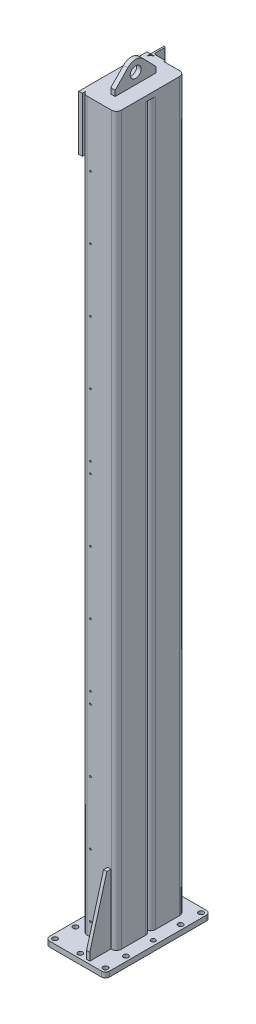
SolidWorks part; units mm, degrees
ref_plane "正面" through (0, 0, 0) normal (0, 0, 1) x (1, 0, 0)
ref_plane "平面" through (0, 0, 0) normal (0, 1, 0) x (1, 0, 0)
ref_plane "右側面" through (0, 0, 0) normal (1, 0, 0) x (0, 0, -1)
ref_plane "平面1" through (0, 19, 0) normal (0, 1, 0) x (1, 0, 0)
sketch "ｽｹｯﾁ2" plane through (0, 19, 0) normal (0, 1, 0) x (1, 0, 0)
  line L0 (44.5, -105) -> (-44.5, -105)
  line L1 (-62.5, -87) -> (-62.5, 2)
  line L2 (-44.5, 20) -> (44.5, 20)
  line L3 (62.5, 2) -> (62.5, -87)
  arc A0 (-44.5, -105) -> (-62.5, -87) centre (-44.5, -87) cw
  arc A1 (-62.5, 2) -> (-44.5, 20) centre (-44.5, 2) cw
  arc A2 (44.5, 20) -> (62.5, 2) centre (44.5, 2) cw
  arc A3 (62.5, -87) -> (44.5, -105) centre (44.5, -87) cw
extrude "ﾎﾞｽ - 押し出し1" add sketch "ｽｹｯﾁ2" along normal blind 2643
sketch "ｽｹｯﾁ3" plane through (0, 19, 0) normal (0, 1, 0) x (1, 0, 0)
  line L0 (44.5, 20) -> (-44.5, 20)
  line L1 (-62.5, 38) -> (-62.5, 127)
  line L2 (-44.5, 145) -> (44.5, 145)
  line L3 (62.5, 127) -> (62.5, 38)
  arc A0 (-44.5, 20) -> (-62.5, 38) centre (-44.5, 38) cw
  arc A1 (-62.5, 127) -> (-44.5, 145) centre (-44.5, 127) cw
  arc A2 (44.5, 145) -> (62.5, 127) centre (44.5, 127) cw
  arc A3 (62.5, 38) -> (44.5, 20) centre (44.5, 38) cw
extrude "ﾎﾞｽ - 押し出し2" add sketch "ｽｹｯﾁ3" along normal blind 2643
sketch "ｽｹｯﾁ4" plane through (0, 19, 0) normal (0, 1, 0) x (1, 0, 0)
  line L0 (44.5, -96) -> (-44.5, -96)
  line L1 (-53.5, -87) -> (-53.5, 2)
  line L2 (-44.5, 11) -> (44.5, 11)
  line L3 (53.5, 2) -> (53.5, -87)
  line L4 (44.5, 29) -> (-44.5, 29)
  line L5 (-53.5, 38) -> (-53.5, 127)
  line L6 (-44.5, 136) -> (44.5, 136)
  line L7 (53.5, 127) -> (53.5, 38)
  arc A0 (-44.5, -96) -> (-53.5, -87) centre (-44.5, -87) cw
  arc A1 (-53.5, 2) -> (-44.5, 11) centre (-44.5, 2) cw
  arc A2 (44.5, 11) -> (53.5, 2) centre (44.5, 2) cw
  arc A3 (53.5, -87) -> (44.5, -96) centre (44.5, -87) cw
  arc A4 (-44.5, 29) -> (-53.5, 38) centre (-44.5, 38) cw
  arc A5 (-53.5, 127) -> (-44.5, 136) centre (-44.5, 127) cw
  arc A6 (44.5, 136) -> (53.5, 127) centre (44.5, 127) cw
  arc A7 (53.5, 38) -> (44.5, 29) centre (44.5, 38) cw
extrude "ｶｯﾄ - 押し出し1" cut sketch "ｽｹｯﾁ4" against normal through all and the other way through all
sketch "ｽｹｯﾁ5" plane through (0, 0, 0) normal (0, 1, 0) x (1, 0, 0)
  line L0 (95, -192.5) -> (-95, -192.5)
  line L1 (-110, -177.5) -> (-110, 177.5)
  line L2 (-95, 192.5) -> (95, 192.5)
  line L3 (110, 177.5) -> (110, -177.5)
  arc A0 (-95, -192.5) -> (-110, -177.5) centre (-95, -177.5) cw
  arc A1 (-110, 177.5) -> (-95, 192.5) centre (-95, 177.5) cw
  arc A2 (95, 192.5) -> (110, 177.5) centre (95, 177.5) cw
  arc A3 (110, -177.5) -> (95, -192.5) centre (95, -177.5) cw
extrude "ﾎﾞｽ - 押し出し3" add sketch "ｽｹｯﾁ5" along normal blind 19
ref_plane "平面2" through (42.5, 0, 0) normal (1, 0, 0) x (0, 0, -1)
sketch "ｽｹｯﾁ7" plane through (42.5, 0, 0) normal (1, 0, 0) x (0, 0, -1)
  line L0 (-105, 19) -> (-105, 272)
  line L1 (-105, 272) -> (-120, 272)
  line L2 (-120, 272) -> (-182.5, 47)
  line L3 (-182.5, 47) -> (-182.5, 19)
  line L4 (-182.5, 19) -> (-105, 19)
extrude "ﾎﾞｽ - 押し出し4" add sketch "ｽｹｯﾁ7" against normal blind 12
sketch "ｽｹｯﾁ8" plane through (0, 19, 0) normal (0, 1, 0) x (1, 0, 0)
  line L0 (-62.5, 145) -> (-12.5, 145)
  line L1 (-12.5, 145) -> (-12.5, 147)
  line L2 (-16.5, 151) -> (-50.5, 151)
  line L3 (-56.5, 157) -> (-56.5, 191)
  line L4 (-60.5, 195) -> (-62.5, 195)
  line L5 (-62.5, 195) -> (-62.5, 145)
  arc A0 (-12.5, 147) -> (-16.5, 151) centre (-16.5, 147) ccw
  arc A1 (-50.5, 151) -> (-56.5, 157) centre (-50.5, 157) cw
  arc A2 (-56.5, 191) -> (-60.5, 195) centre (-60.5, 191) ccw
extrude "ﾎﾞｽ - 押し出し5" add sketch "ｽｹｯﾁ8" along normal blind 2662
ref_plane "平面3" through (0, 169, 0) normal (0, 1, 0) x (1, 0, 0)
sketch "ｽｹｯﾁ10" plane through (0, 169, 0) normal (0, 1, 0) x (1, 0, 0)
  line L0 (-62.5, -40) -> (-74.5, -40)
  line L1 (-74.5, -40) -> (-74.5, -27.5)
  line L2 (-74.5, -27.5) -> (-70.5, -27.5)
  line L3 (-70.5, -27.5) -> (-70.5, 35)
  line L4 (-70.5, 35) -> (-62.5, 35)
  line L5 (-62.5, 35) -> (-62.5, -40)
extrude "ﾎﾞｽ - 押し出し6" add sketch "ｽｹｯﾁ10" along normal blind 2190
ref_plane "平面4" through (0, 2662, 0) normal (0, 1, 0) x (1, 0, 0)
sketch "ｽｹｯﾁ12" plane through (0, 2662, 0) normal (0, 1, 0) x (1, 0, 0)
  line L0 (44.5, -105) -> (-44.5, -105)
  line L1 (-62.5, -87) -> (-62.5, 127)
  line L2 (-44.5, 145) -> (44.5, 145)
  line L3 (62.5, 127) -> (62.5, -87)
  arc A0 (-44.5, -105) -> (-62.5, -87) centre (-44.5, -87) cw
  arc A1 (-62.5, 127) -> (-44.5, 145) centre (-44.5, 127) cw
  arc A2 (44.5, 145) -> (62.5, 127) centre (44.5, 127) cw
  arc A3 (62.5, -87) -> (44.5, -105) centre (44.5, -87) cw
extrude "ﾎﾞｽ - 押し出し7" add sketch "ｽｹｯﾁ12" along normal blind 19
ref_plane "平面5" through (-62.5, 0, 0) normal (1, 0, 0) x (0, 0, -1)
sketch "ｽｹｯﾁ14" plane through (-62.5, 0, 0) normal (1, 0, 0) x (0, 0, -1)
  line L0 (-105, 2481) -> (144.98, 2481)
  line L1 (144.98, 2481) -> (144.98, 2681)
  line L2 (144.98, 2681) -> (-105, 2681)
  line L3 (-105, 2681) -> (-105, 2481)
extrude "ﾎﾞｽ - 押し出し8" add sketch "ｽｹｯﾁ14" against normal blind 13
sketch "ｽｹｯﾁ15" plane through (0, 0, 0) normal (1, 0, 0) x (0, 0, -1)
  line L0 (-55, 2681) -> (95, 2681)
  line L1 (95, 2681) -> (95, 2701)
  line L2 (95, 2701) -> (48.7496, 2748.8111)
  line L3 (-8.7496, 2748.8111) -> (-55, 2701)
  line L4 (-55, 2701) -> (-55, 2681)
  arc A0 (48.7496, 2748.8111) -> (-8.7496, 2748.8111) centre (20, 2721) ccw
extrude "ﾎﾞｽ - 押し出し9" add sketch "ｽｹｯﾁ15" against normal blind 8 and the other way blind 8
sketch "ｽｹｯﾁ16" plane through (0, 0, 0) normal (0, 1, 0) x (1, 0, 0)
  circle A0 centre (92.5, -175) radius 9
  circle A1 centre (0, -175) radius 9
  circle A2 centre (-92.5, -175) radius 9
  circle A3 centre (92.5, -100) radius 9
  circle A4 centre (-92.5, -100) radius 9
  circle A5 centre (92.5, 100) radius 9
  circle A6 centre (-92.5, 100) radius 9
  circle A7 centre (92.5, 175) radius 9
  circle A8 centre (0, 175) radius 9
  circle A9 centre (-92.5, 175) radius 9
sketch "ｽｹｯﾁ17" plane through (0, 0, 0) normal (0, 1, 0) x (1, 0, 0)
  circle A0 centre (92.5, -175) radius 9
  circle A1 centre (0, -175) radius 9
  circle A2 centre (-92.5, -175) radius 9
  circle A3 centre (92.5, -100) radius 9
  circle A4 centre (-92.5, -100) radius 9
  circle A5 centre (92.5, 100) radius 9
  circle A6 centre (-92.5, 100) radius 9
  circle A7 centre (92.5, 175) radius 9
  circle A8 centre (0, 175) radius 9
  circle A9 centre (-92.5, 175) radius 9
extrude "ｶｯﾄ - 押し出し3" cut sketch "ｽｹｯﾁ17" along normal blind 19
sketch "ｽｹｯﾁ18" plane through (0, 0, 0) normal (0, 1, 0) x (1, 0, 0)
  circle A0 centre (92.5, 0) radius 8
  circle A1 centre (-92.5, 0) radius 8
sketch "ｽｹｯﾁ19" plane through (0, 0, 0) normal (0, 1, 0) x (1, 0, 0)
  circle A0 centre (92.5, 0) radius 8
  circle A1 centre (-92.5, 0) radius 8
extrude "ｶｯﾄ - 押し出し5" cut sketch "ｽｹｯﾁ19" along normal blind 19
sketch "ｽｹｯﾁ20" plane through (0, 0, 0) normal (1, 0, 0) x (0, 0, -1)
  circle A0 centre (-85, 2531) radius 8
  circle A1 centre (125, 2531) radius 8
  circle A2 centre (-85, 2631) radius 8
  circle A3 centre (125, 2631) radius 8
extrude "ｶｯﾄ - 押し出し6" cut sketch "ｽｹｯﾁ20" against normal blind 75.5
sketch "ｽｹｯﾁ21" plane through (0, 0, 0) normal (1, 0, 0) x (0, 0, -1)
  circle A0 centre (-85, 2581) radius 8
  circle A1 centre (125, 2581) radius 8
extrude "ｶｯﾄ - 押し出し7" cut sketch "ｽｹｯﾁ21" against normal blind 75.5
sketch "ｽｹｯﾁ22" plane through (0, 0, 0) normal (1, 0, 0) x (0, 0, -1)
  circle A0 centre (-5, 214.5) radius 6
  circle A1 centre (-5, 319.5) radius 6
  circle A2 centre (-5, 424.5) radius 6
  circle A3 centre (-5, 529.5) radius 6
  circle A4 centre (-5, 634.5) radius 6
  circle A5 centre (-5, 739.5) radius 6
  circle A6 centre (-5, 844.5) radius 6
  circle A7 centre (-5, 949.5) radius 6
  circle A8 centre (-5, 1054.5) radius 6
  circle A9 centre (-5, 1159.5) radius 6
  circle A10 centre (-5, 1264.5) radius 6
  circle A11 centre (-5, 1369.5) radius 6
  circle A12 centre (-5, 1474.5) radius 6
  circle A13 centre (-5, 1579.5) radius 6
  circle A14 centre (-5, 1684.5) radius 6
  circle A15 centre (-5, 1789.5) radius 6
  circle A16 centre (-5, 1894.5) radius 6
  circle A17 centre (-5, 1999.5) radius 6
  circle A18 centre (-5, 2104.5) radius 6
  circle A19 centre (-5, 2209.5) radius 6
  circle A20 centre (-5, 2314.5) radius 6
extrude "ｶｯﾄ - 押し出し8" cut sketch "ｽｹｯﾁ22" against normal blind 70.5
sketch "ｽｹｯﾁ23" plane through (0, 0, 0) normal (0, 0, 1) x (1, 0, 0)
  circle A0 centre (-32.5, 2448.5) radius 3
  circle A1 centre (-32.5, 2218.5) radius 3
  circle A2 centre (-32.5, 1988.5) radius 3
  circle A3 centre (-32.5, 1758.5) radius 3
  circle A4 centre (-32.5, 1528.5) radius 3
  circle A5 centre (-32.5, 1488.5) radius 3
  circle A6 centre (-32.5, 1258.5) radius 3
  circle A7 centre (-32.5, 1028.5) radius 3
  circle A8 centre (-32.5, 798.5) radius 3
  circle A9 centre (-32.5, 758.5) radius 3
  circle A10 centre (-32.5, 528.5) radius 3
  circle A11 centre (-32.5, 298.5) radius 3
  circle A12 centre (-32.5, 68.5) radius 3
sketch "ｽｹｯﾁ24" plane through (0, 0, 0) normal (0, 0, 1) x (1, 0, 0)
  circle A0 centre (-32.5, 2448.5) radius 3
  circle A1 centre (-32.5, 2218.5) radius 3
  circle A2 centre (-32.5, 1988.5) radius 3
  circle A3 centre (-32.5, 1758.5) radius 3
  circle A4 centre (-32.5, 1528.5) radius 3
  circle A5 centre (-32.5, 1488.5) radius 3
  circle A6 centre (-32.5, 1258.5) radius 3
  circle A7 centre (-32.5, 1028.5) radius 3
  circle A8 centre (-32.5, 798.5) radius 3
  circle A9 centre (-32.5, 758.5) radius 3
  circle A10 centre (-32.5, 528.5) radius 3
  circle A11 centre (-32.5, 298.5) radius 3
  circle A12 centre (-32.5, 68.5) radius 3
extrude "ｶｯﾄ - 押し出し10" cut sketch "ｽｹｯﾁ24" along normal blind 105
sketch "ｽｹｯﾁ25" plane through (0, 0, 0) normal (1, 0, 0) x (0, 0, -1)
  circle A0 centre (180, 60) radius 3
  circle A1 centre (180, 480) radius 3
  circle A2 centre (180, 900) radius 3
  circle A3 centre (180, 1320) radius 3
  circle A4 centre (180, 1740) radius 3
  circle A5 centre (180, 2160) radius 3
  circle A6 centre (180, 2580) radius 3
extrude "ｶｯﾄ - 押し出し11" cut sketch "ｽｹｯﾁ25" against normal blind 62.5
sketch "ｽｹｯﾁ26" plane through (0, 0, 0) normal (1, 0, 0) x (0, 0, -1)
  circle A0 centre (20, 2721) radius 20
extrude "ｶｯﾄ - 押し出し12" cut sketch "ｽｹｯﾁ26" against normal through all and the other way through all
